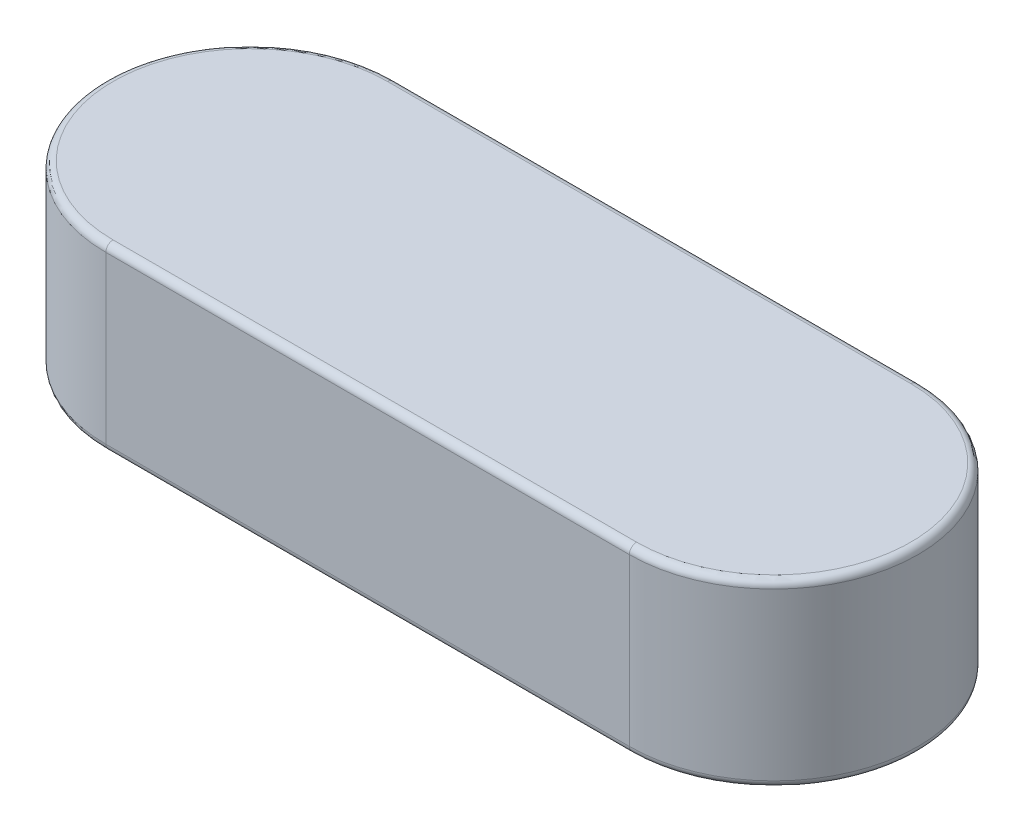
SolidWorks part; units mm, degrees
ref_plane "Front Plane" through (0, 0, 0) normal (0, 0, 1) x (1, 0, 0)
ref_plane "Top Plane" through (0, 0, 0) normal (0, 1, 0) x (1, 0, 0)
ref_plane "Right Plane" through (0, 0, 0) normal (1, 0, 0) x (0, 0, -1)
sketch "Sketch1" plane through (0, 0, 0) normal (0, 1, 0) x (1, 0, 0)
  line L1 (-29, 8) -> (0, 8)
  line L3 (-29, -8) -> (0, -8)
  arc A0 (0, -8) -> (0, 8) centre (0, 0) ccw
  arc A1 (-29, 8) -> (-29, -8) centre (-29, 0) ccw
  dimension "l" = 45
  dimension "b" = 16
extrude "Extrude1" add sketch "Sketch1" along normal blind 10
fillet "Fillet1" radius 0.4 8 edges at (-14.5, 0, -8) (8, 0, 0) (-37, 0, 0) (-14.5, 0, 8) (8, 10, 0) (-14.5, 10, 8) (-14.5, 10, -8) (-37, 10, 0)
